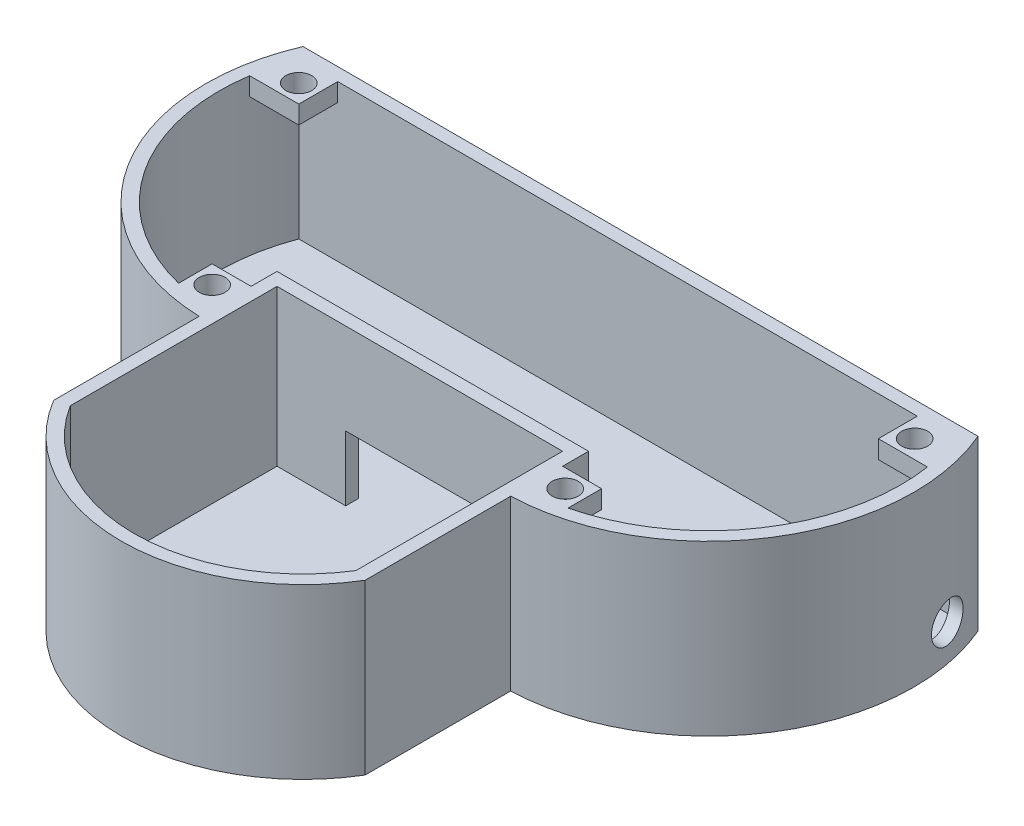
SolidWorks part; units mm, degrees
ref_plane "Alzado" through (0, 0, 0) normal (0, 0, 1) x (1, 0, 0)
ref_plane "Planta" through (0, 0, 0) normal (0, 1, 0) x (1, 0, 0)
ref_plane "Vista lateral" through (0, 0, 0) normal (1, 0, 0) x (0, 0, -1)
sketch "Croquis2" plane through (0, 0, 0) normal (0, 1, 0) x (1, 0, 0)
  line L1 (130, -55) -> (60, -55)
  line L3 (130, 55) -> (-130, 55)
  line L5 (130, -55) -> (-130, 55) construction
  line L6 (130, 55) -> (-130, -55) construction
  line L10 (-60, -55) -> (-60, -35)
  line L11 (-60, -35) -> (60, -35)
  line L12 (60, -55) -> (60, -35)
  line L14 (-60, -55) -> (-60, -111.06)
  line L15 (-60, -111.06) -> (60, -111.06)
  line L16 (60, -55) -> (60, -111.06)
  line L19 (-60, -55) -> (-130, -55)
  arc A2 (-93.9624, -39.7533) -> (-60, -55) centre (-40, 35) ccw
  arc A4 (-130, 55) -> (-60, -55) centre (-57.3553, 23.9557) ccw
  arc A5 (60, -55) -> (130, 55) centre (57.3553, 23.9557) ccw
  arc A6 (-60, -111.06) -> (60, -111.06) centre (0, -75.0045) ccw
  point P0 (0, 0)
  dimension "D5" = 20
  dimension "D6" = 120
  dimension "D7" = 56.06
  dimension "D8" = 79
  dimension "D3" = 79
  dimension "D1" = 110
  dimension "D2" = 260
  dimension "D4" = 120
extrude "Saliente-Extruir1" add sketch "Croquis2" along normal blind 65
shell "Vaciado1" thickness 5
sketch "Croquis3" plane through (0, 5, 0) normal (0, 1, 0) x (1, 0, 0)
  line L0 (55, -50.0068) -> (55, -109.6455) construction
  line L1 (-55, -50.0068) -> (55, -50.0068)
  line L2 (-55, -50.0068) -> (-55, -30.0068)
  line L3 (-55, -30.0068) -> (55, -30.0068)
  line L4 (55, -50.0068) -> (55, -30.0068)
  line L5 (-60, -49.997) -> (-60, -25.0068)
  line L6 (-60, -25.0068) -> (60, -25.0068)
  line L7 (60, -25.0068) -> (60, -49.997)
  arc A0 (-126.6207, 50) -> (-55, -50.0068) centre (-57.3553, 23.9557) ccw construction
  arc A1 (55, -50.0068) -> (126.6207, 50) centre (57.3553, 23.9557) ccw construction
  arc M6 (-126.6207, 50) -> (-55, -50.0068) centre (-57.3553, 23.9557) ccw
  arc M10 (55, -50.0068) -> (126.6207, 50) centre (57.3553, 23.9557) ccw
  dimension "D1" = 20
  dimension "D2" = 0
  dimension "D3" = 5
extrude "Saliente-Extruir2" add sketch "Croquis3" along normal blind 60 contours L7 L6 L5 L2 L3 L4 M6 M10
sketch "Croquis4" plane through (0, 0, 30.0068) normal (0, 0, 1) x (1, 0, 0)
  line L0 (-55, 5) -> (55, 5) construction
  line L1 (-28.5502, 5) -> (31.9042, 5)
  line L2 (-28.5502, 5) -> (-28.5502, 30)
  line L3 (-28.5502, 30) -> (31.9042, 30)
  line L4 (31.9042, 5) -> (31.9042, 30)
  dimension "D1" = 25
extrude "Cortar-Extruir1" cut sketch "Croquis4" against normal blind 65
ref_plane "Plano1" through (130, 0, 0) normal (1, 0, 0) x (0, 0, -1)
sketch "Croquis5" plane through (130, 0, 0) normal (1, 0, 0) x (0, 0, -1)
  circle A0 centre (38.5432, 13.712) radius 7.5
  dimension "D1" = 15
extrude "Cortar-Extruir2" cut sketch "Croquis5" against normal blind 75 and the other way blind 65
sketch "Croquis6" plane through (0, 65, 0) normal (0, 1, 0) x (1, 0, 0)
  line L0 (-126.6207, 50) -> (-111.6207, 50)
  line L1 (126.6207, 50) -> (-126.6207, 50) construction
  line L2 (-111.6207, 50) -> (-111.6207, 35)
  line L3 (-111.6207, 35) -> (-130.5265, 35)
  arc A0 (-126.6207, 50) -> (-60, -49.997) centre (-57.3553, 23.9557) ccw construction
  arc A1 (-130.5265, 35) -> (-126.6207, 50) centre (-57.3553, 23.9557) cw
  dimension "D1" = 15
  dimension "D2" = 15
extrude "Saliente-Extruir3" add sketch "Croquis6" against normal blind 7
sketch "Croquis8" plane through (0, 65, 0) normal (0, 1, 0) x (1, 0, 0)
  line L0 (126.6207, 50) -> (111.6207, 50)
  line L1 (126.6207, 50) -> (-111.6207, 50) construction
  line L2 (111.6207, 50) -> (111.6207, 35)
  line L3 (111.6207, 35) -> (130.5265, 35)
  arc A1 (60, -49.997) -> (126.6207, 50) centre (57.3553, 23.9557) ccw construction
  arc A2 (130.5265, 35) -> (126.6207, 50) centre (57.3553, 23.9557) ccw
  dimension "D1" = 15
  dimension "D2" = 15
extrude "Saliente-Extruir5" add sketch "Croquis8" against normal blind 7
sketch "Croquis10" plane through (0, 65, 0) normal (0, 1, 0) x (1, 0, 0)
  line L0 (-60, -49.997) -> (-60, -34.997)
  line L1 (-60, -49.997) -> (-60, -25.0068) construction
  line L2 (-60, -34.997) -> (-75, -34.997)
  line L3 (-75, -34.997) -> (-75, -47.9099)
  arc A0 (-130.5265, 35) -> (-60, -49.997) centre (-57.3553, 23.9557) ccw construction
  arc A1 (-75, -47.9099) -> (-60, -49.997) centre (-57.3553, 23.9557) ccw
  dimension "D1" = 15
  dimension "D2" = 15
extrude "Saliente-Extruir7" add sketch "Croquis10" against normal blind 7
sketch "Croquis11" plane through (0, 65, 0) normal (0, 1, 0) x (1, 0, 0)
  line L0 (60, -49.997) -> (60, -34.997)
  line L1 (60, -25.0068) -> (60, -49.997) construction
  line L2 (60, -34.997) -> (75, -34.997)
  line L3 (75, -34.997) -> (75, -47.9099)
  arc A0 (60, -49.997) -> (130.5265, 35) centre (57.3553, 23.9557) ccw construction
  arc A1 (75, -47.9099) -> (60, -49.997) centre (57.3553, 23.9557) cw
  dimension "D1" = 15
  dimension "D2" = 15
extrude "Saliente-Extruir8" add sketch "Croquis11" against normal blind 7
sketch "Croquis12" plane through (0, 65, 0) normal (0, 1, 0) x (1, 0, 0)
  line L0 (-60, -34.997) -> (-75, -34.997) construction
  line L1 (75, -47.9099) -> (75, -34.997) construction
  line L2 (75, -34.997) -> (60, -34.997) construction
  line L3 (111.6207, 50) -> (111.6207, 35) construction
  line L4 (111.6207, 35) -> (130.5265, 35) construction
  line L5 (-111.6207, 35) -> (-111.6207, 50) construction
  line L6 (-130.5265, 35) -> (-111.6207, 35) construction
  circle A0 centre (-68, -41.997) radius 5
  circle A1 centre (-118.6207, 42) radius 5
  circle A2 centre (118.6207, 42) radius 5
  circle A3 centre (68, -41.997) radius 5
  dimension "D1" = 10
  dimension "D2" = 7
  dimension "D6" = 10
  dimension "D7" = 10
  dimension "D9" = 7
  dimension "D10" = 10
  dimension "D11" = 7
  dimension "D12" = 7
  dimension "D3" = 7
  dimension "D4" = 7
  dimension "D5" = 7
  dimension "D8" = 7
extrude "Cortar-Extruir3" cut sketch "Croquis12" against normal blind 8
